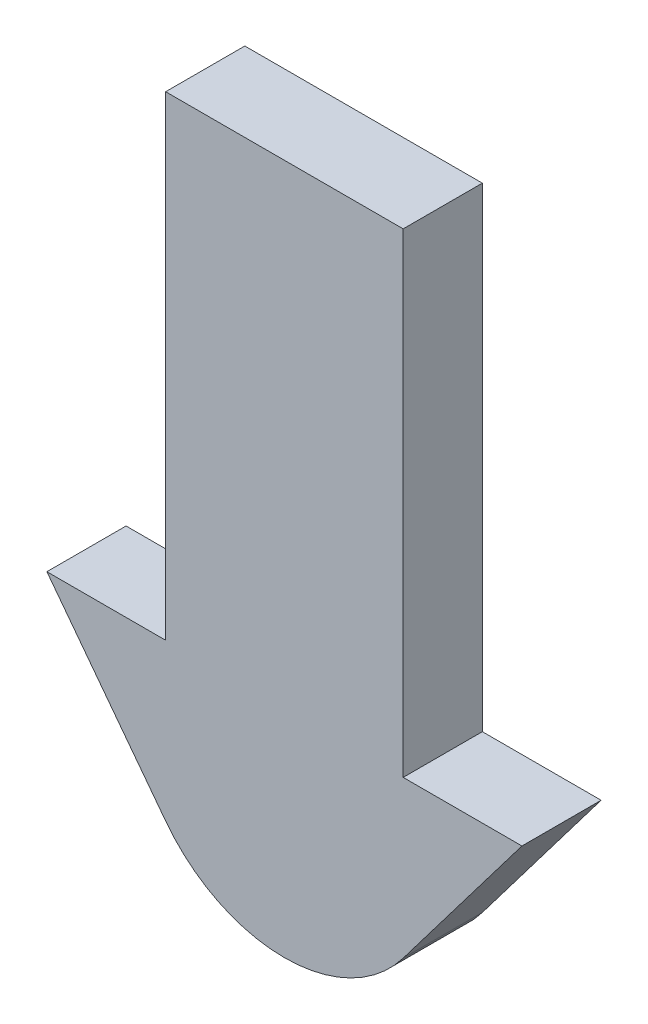
SolidWorks part; units mm, degrees
ref_plane "Front Plane" through (0, 0, 0) normal (0, 0, 1) x (1, 0, 0)
ref_plane "Top Plane" through (0, 0, 0) normal (0, 1, 0) x (1, 0, 0)
ref_plane "Right Plane" through (0, 0, 0) normal (1, 0, 0) x (0, 0, -1)
other "Configuration Table"
sketch "Sketch1" plane through (0, 0, 0) normal (0, 0, 1) x (1, 0, 0)
  line L0 (-15, 90) -> (15, 90)
  line L1 (-15, 90) -> (-15, 30)
  line L2 (15, 90) -> (15, 30)
  line L3 (-15, 30) -> (-30, 30)
  line L4 (15, 30) -> (30, 30)
  line L5 (-30, 30) -> (-15, 10.2284)
  line L6 (30, 30) -> (15, 10.2284)
  arc A1 (-15, 10.2284) -> (15, 10.2284) centre (0, 21.6083) ccw
extrude "Boss-Extrude1" add sketch "Sketch1" along normal blind 10
